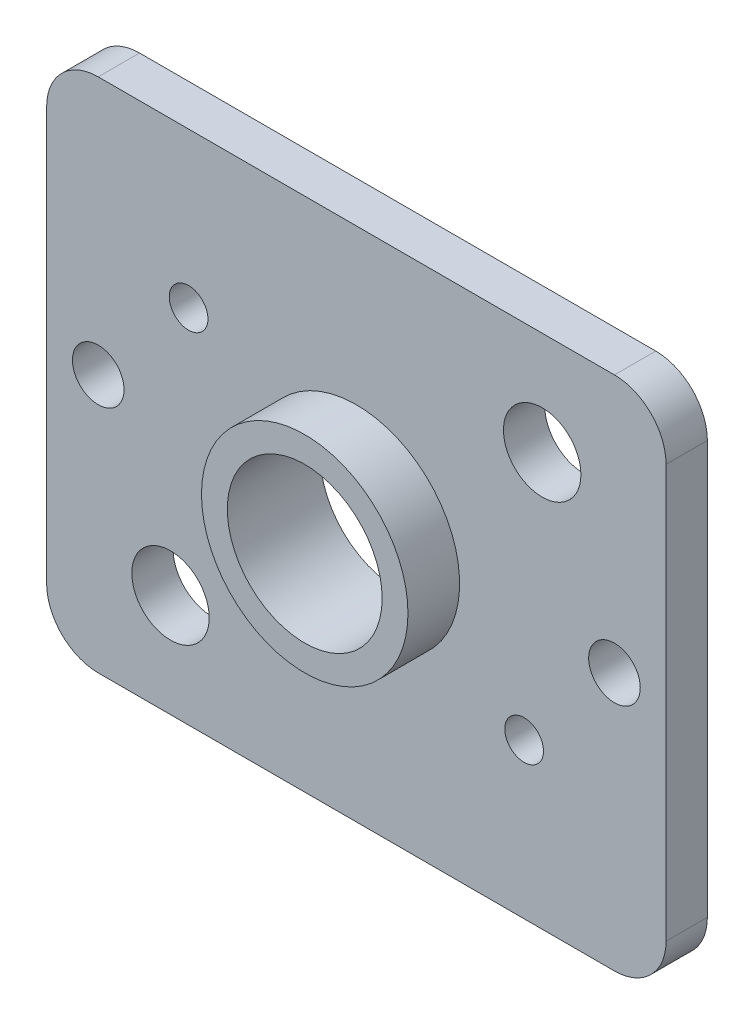
SolidWorks part; units mm, degrees
material "Латунь"
ref_plane "Спереди" through (0, 0, 0) normal (0, 0, 1) x (1, 0, 0)
ref_plane "Сверху" through (0, 0, 0) normal (0, 1, 0) x (1, 0, 0)
ref_plane "Справа" through (0, 0, 0) normal (1, 0, 0) x (0, 0, -1)
sketch "Эскиз1" plane through (0, 0, 0) normal (0, 0, 1) x (1, 0, 0)
  line L1 (-6, -5) -> (6, -5)
  line L2 (-6, -5) -> (-6, 5)
  line L3 (-6, 5) -> (6, 5)
  line L4 (6, -5) -> (6, 5)
  line L5 (-6, -5) -> (6, 5) construction
  line L6 (-6, 5) -> (6, -5) construction
  point P0 (0, 0)
  dimension "D1" = 12
  dimension "D2" = 10
extrude "Бобышка-Вытянуть1" add sketch "Эскиз1" along normal blind 0.8
sketch "Эскиз2" plane through (0, 0, 0.8) normal (0, 0, 1) x (1, 0, 0)
  line L0 (-6, -5) -> (6, 5) construction
  line L1 (-6, -5) -> (6, -5) construction
  line L2 (-6, 0) -> (6, 0) construction
  line L3 (-6, 5) -> (-6, -5) construction
  line L4 (6, 5) -> (-6, 5) construction
  line L5 (6, -5) -> (6, 5) construction
  circle A0 centre (0, 0) radius 1.5
  circle A1 centre (-3.6, -3) radius 0.75
  circle A2 centre (3.6, 3) radius 0.75
  circle A3 centre (3.25, -2) radius 0.375
  circle A4 centre (-3.25, 2) radius 0.375
  point P27 (0, 0)
  dimension "D1" = 3
  dimension "D3" = 1.5
  dimension "D5" = 1.5
  dimension "D8" = 0.75
  dimension "D9" = 2
  dimension "D2" = 2
  dimension "D4" = 2
  dimension "D6" = 2.75
  dimension "D7" = 3
extrude "Вырез-Вытянуть1" cut sketch "Эскиз2" against normal up to next
fillet "Скругление1" radius 1 4 edges at (6, -5, 0.4) (-6, -5, 0.4) (-6, 5, 0.4) (6, 5, 0.4)
sketch "Эскиз5" plane through (0, 0, 0.8) normal (0, 0, 1) x (1, 0, 0)
  line L1 (-6, 4) -> (-6, -4) construction
  line L3 (-6, 0) -> (6, 0) construction
  line L4 (6, -4) -> (6, 4) construction
  circle A0 centre (5, 0) radius 0.5
  circle A1 centre (-5, 0) radius 0.5
  dimension "D1" = 1
  dimension "D2" = 1
  dimension "D4" = 1
  dimension "D3" = 1
extrude "Вырез-Вытянуть2" cut sketch "Эскиз5" against normal through all
sketch "Эскиз14" plane through (0, 0, 0.8) normal (0, 0, 1) x (1, 0, 0)
  circle A0 centre (0, 0) radius 1.5 construction
  circle A1 centre (0, 0) radius 1.5
  circle A2 centre (0, 0) radius 2
  dimension "D1" = 0.5
extrude "Бобышка-Вытянуть2" add sketch "Эскиз14" along normal blind 1
